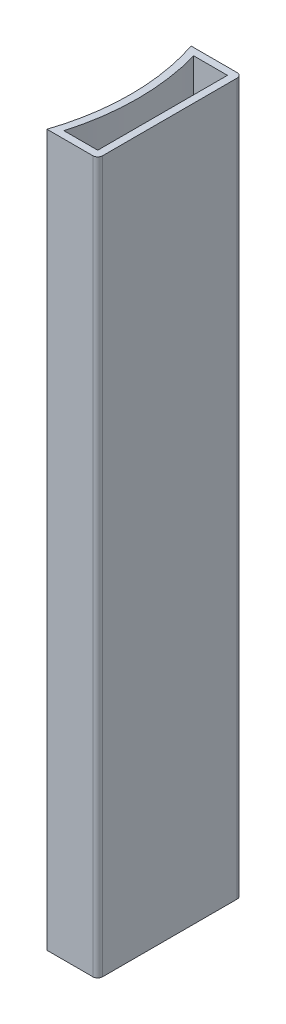
SolidWorks part; units mm, degrees
ref_plane "Front Plane" through (0, 0, 0) normal (0, 0, 1) x (1, 0, 0)
ref_plane "Top Plane" through (0, 0, 0) normal (0, 1, 0) x (1, 0, 0)
ref_plane "Right Plane" through (0, 0, 0) normal (1, 0, 0) x (0, 0, -1)
sketch "Sketch1" plane through (0, 0, 0) normal (0, 1, 0) x (1, 0, 0)
  line L0 (0, 0) -> (10.57, 0)
  line L1 (10.57, 0) -> (10.57, -30)
  line L2 (10.57, -30) -> (0, -30)
  line L3 (10.57, -15) -> (0, -15) construction
  arc A1 (0, -30) -> (0, 0) centre (-45, -15) ccw
  dimension "D2" = 10.57
  dimension "D1" = 15
extrude "Boss-Extrude1" add sketch "Sketch1" along normal blind 148
fillet "Fillet1" radius 1 2 edges at (10.57, 74, 0) (10.57, 74, 30)
shell "Shell1" thickness 1.5
